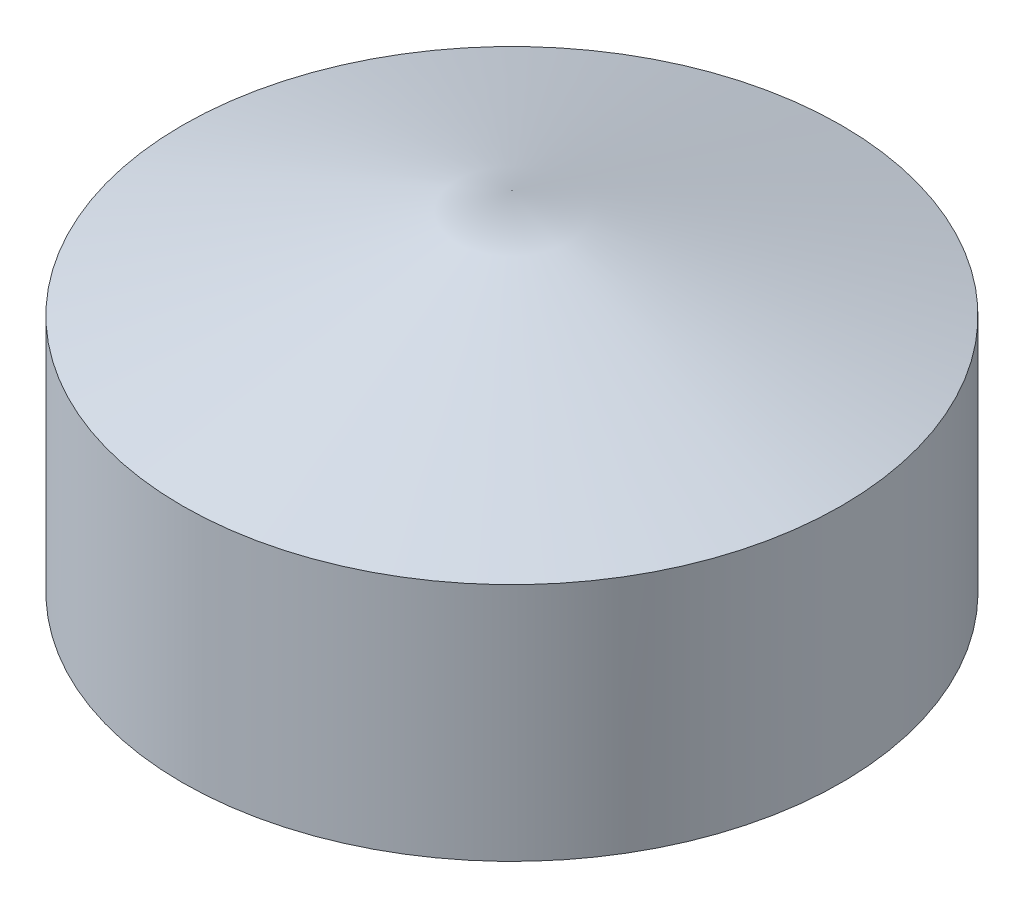
SolidWorks part; units mm, degrees
ref_plane "Ön Düzlem" through (0, 0, 0) normal (0, 0, 1) x (1, 0, 0)
ref_plane "Üst Düzlem" through (0, 0, 0) normal (0, 1, 0) x (1, 0, 0)
ref_plane "Sağ Düzlem" through (0, 0, 0) normal (1, 0, 0) x (0, 0, -1)
sketch "Çizim1" plane through (0, 0, 0) normal (0, 1, 0) x (1, 0, 0)
  circle A0 centre (0, 0) radius 11
  circle A1 centre (0, 0) radius 10
  dimension "D1" = 22
  dimension "D2" = 20
extrude "Yükseklik-Ekstrüzyon1" add sketch "Çizim1" along normal blind 8
sketch "Çizim2" plane through (0, 0, 0) normal (0, 0, 1) x (1, 0, 0)
  line L1 (0, 11.6127) -> (11, 8)
  line L2 (0, 11.6127) -> (0, 8)
  line L6 (11, 8) -> (-11, 8) construction
  line L7 (0, 8) -> (11, 8)
revolve "Döndür1" add sketch "Çizim2" angle 360 about L2
